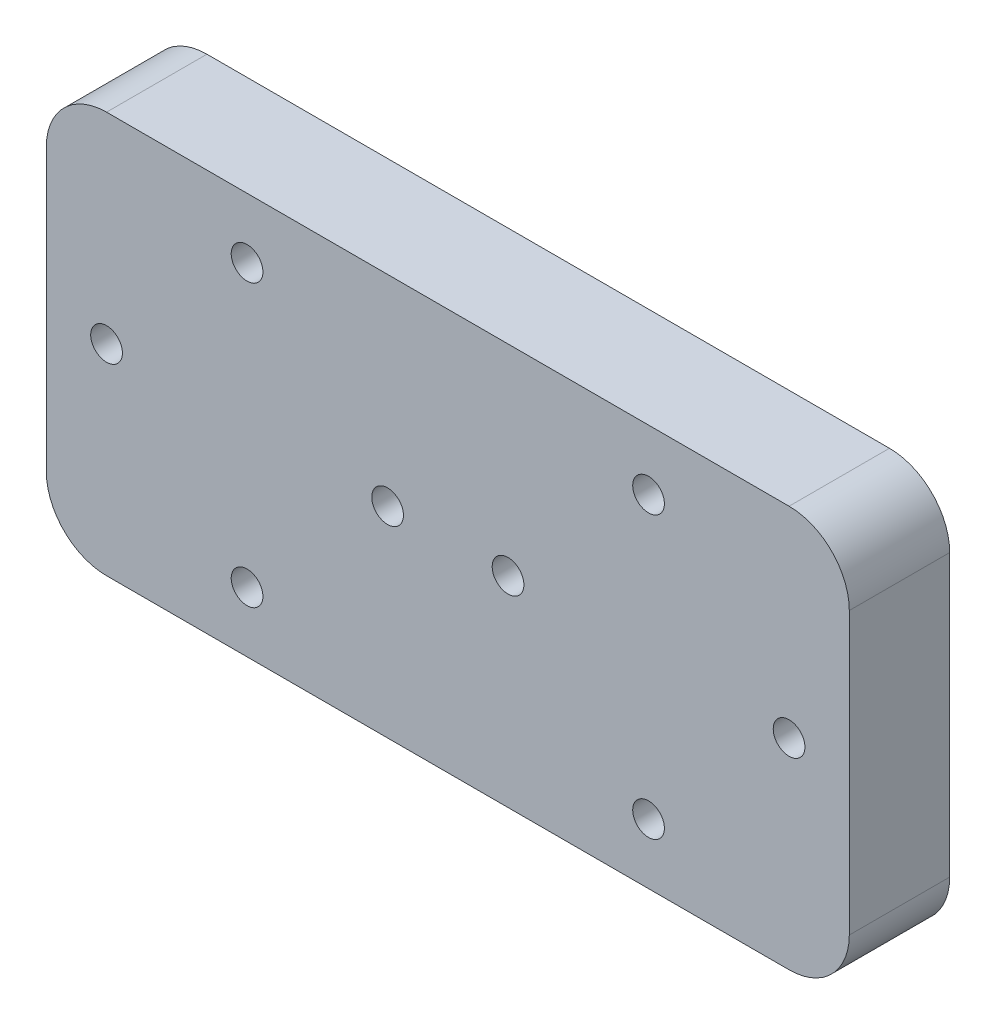
SolidWorks part; units mm, degrees
ref_plane "Plan de face" through (0, 0, 0) normal (0, 0, 1) x (1, 0, 0)
ref_plane "Plan de dessus" through (0, 0, 0) normal (0, 1, 0) x (1, 0, 0)
ref_plane "Plan de droite" through (0, 0, 0) normal (1, 0, 0) x (0, 0, -1)
sketch "Esquisse1" plane through (0, 0, 0) normal (0, 0, 1) x (1, 0, 0)
  line L1 (0, 0) -> (40, 0)
  line L2 (0, 0) -> (0, 20)
  line L3 (0, 20) -> (40, 20)
  line L4 (40, 0) -> (40, 20)
  dimension "D1" = 20
  dimension "D2" = 40
extrude "Boss.-Extru.1" add sketch "Esquisse1" along normal blind 5
fillet "Congé1" radius 3 4 edges at (0, 0, 2.5) (0, 20, 2.5) (40, 0, 2.5) (40, 20, 2.5)
sketch "Esquisse2" plane through (0, 0, 5) normal (0, 0, 1) x (1, 0, 0)
  line L0 (0, 17) -> (0, 3) construction
  line L1 (0, 10) -> (40, 10) construction
  line L2 (40, 3) -> (40, 17) construction
  line L3 (20, 20) -> (20, 0) construction
  line L4 (37, 20) -> (3, 20) construction
  line L5 (3, 0) -> (37, 0) construction
  line L6 (10, 19.6799) -> (10, 4.7021) construction
  circle A0 centre (3, 10) radius 0.79
  circle A1 centre (10, 17) radius 0.79
  circle A2 centre (10, 3) radius 0.79
  circle A3 centre (17, 10) radius 0.79
  circle A4 centre (23, 10) radius 0.79
  circle A5 centre (30, 3) radius 0.79
  circle A6 centre (30, 17) radius 0.79
  circle A7 centre (37, 10) radius 0.79
  point P22 (0, 0)
  point P23 (0, 0)
  dimension "D1" = 3
  dimension "D2" = 1.58
  dimension "D3" = 1.58
  dimension "D4" = 1.58
  dimension "D5" = 1.58
  dimension "D6" = 14
  dimension "D7" = 14
  dimension "D8" = 3
extrude "Enlèv. mat.-Extru.1" cut sketch "Esquisse2" against normal through all
